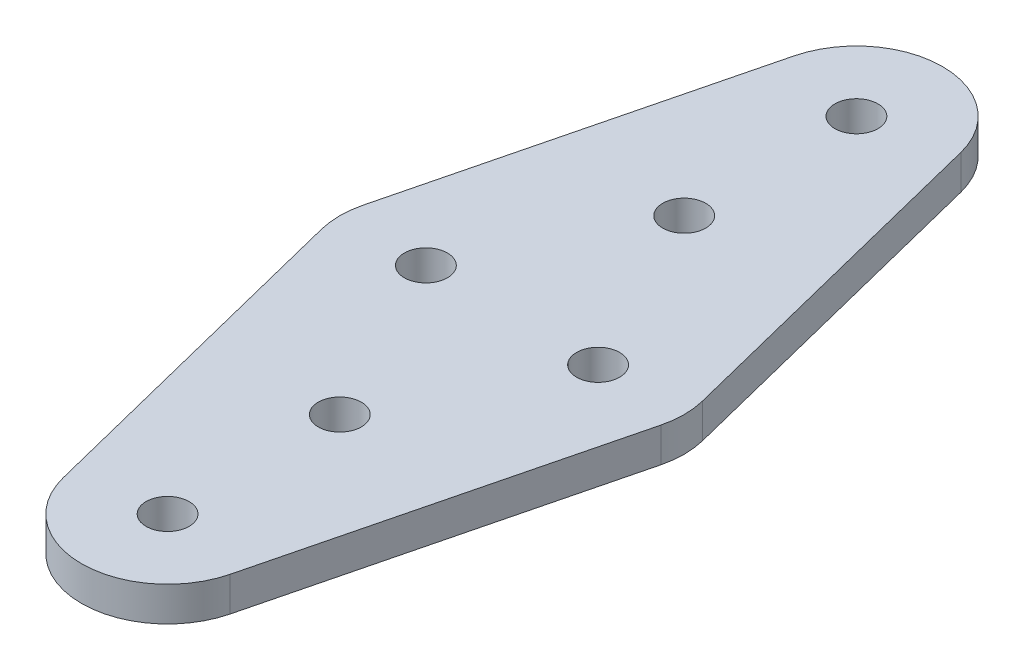
SolidWorks part; units mm, degrees
material "PA Type 6"
ref_plane "Front Plane" through (0, 0, 0) normal (0, 0, 1) x (1, 0, 0)
ref_plane "Top Plane" through (0, 0, 0) normal (0, 1, 0) x (1, 0, 0)
ref_plane "Right Plane" through (0, 0, 0) normal (1, 0, 0) x (0, 0, -1)
sketch "Sketch1" plane through (0, 0, 0) normal (0, 1, 0) x (1, 0, 0)
  line L0 (0, 48.5704) -> (0, -31.4177) construction
  line L1 (-41.6317, 0) -> (40.9422, 0) construction
  line L2 (-9.7014, 42.4254) -> (-19.7014, 2.4254)
  line L4 (9.7014, 42.4254) -> (19.7014, 2.4254)
  line L5 (9.7014, -42.4254) -> (19.7014, -2.4254)
  line L6 (-9.7014, -42.4254) -> (-19.7014, -2.4254)
  circle A0 centre (10, 0) radius 2.5
  circle A1 centre (-10, 0) radius 2.5
  circle A2 centre (0, 20) radius 2.5
  circle A3 centre (0, 40) radius 2.5
  arc A4 (9.7014, 42.4254) -> (-9.7014, 42.4254) centre (0, 40) ccw
  arc A5 (-19.7014, 2.4254) -> (-19.7014, -2.4254) centre (-10, 0) ccw
  arc A6 (19.7014, -2.4254) -> (19.7014, 2.4254) centre (10, 0) ccw
  circle A7 centre (0, -20) radius 2.5
  circle A8 centre (0, -40) radius 2.5
  arc A9 (9.7014, -42.4254) -> (-9.7014, -42.4254) centre (0, -40) cw
  point P27 (19.7014, -2.4254)
  dimension "D1" = 5
  dimension "D3" = 5
  dimension "D5" = 5
  dimension "D7" = 20
  dimension "D8" = 20
  dimension "D9" = 20
  dimension "D2" = 10
  dimension "D4" = 20
  dimension "D6" = 40
extrude "Boss-Extrude1" add sketch "Sketch1" along normal blind 4
